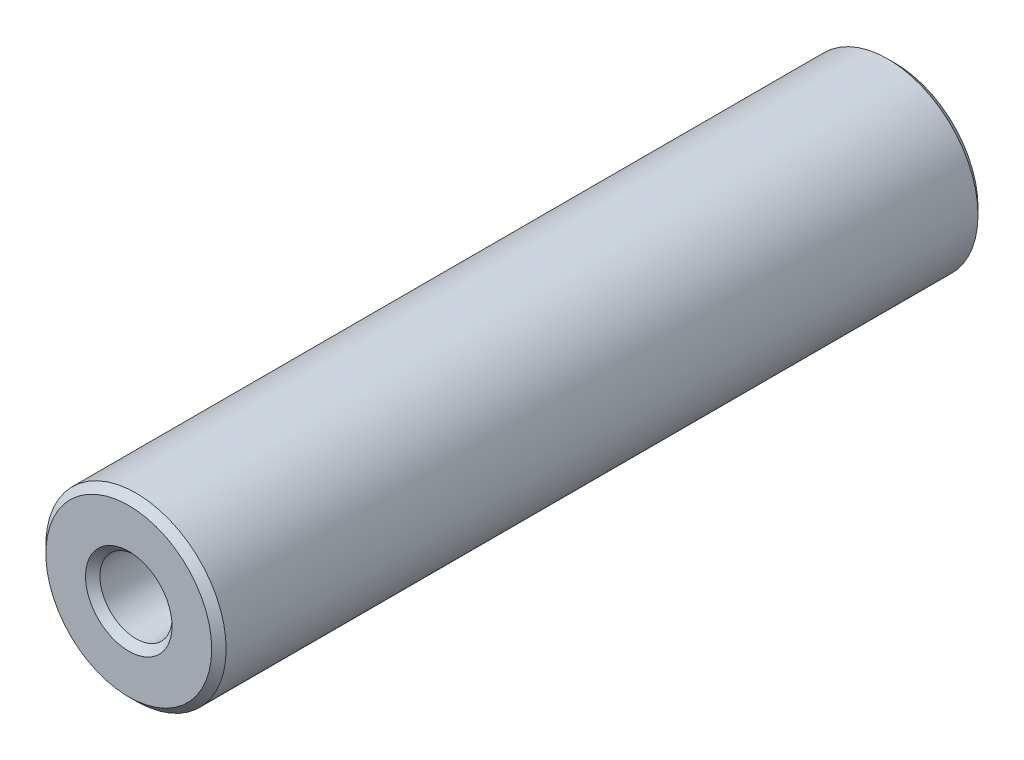
SolidWorks part; units mm, degrees
ref_plane "Front Plane" through (0, 0, 0) normal (0, 0, 1) x (1, 0, 0)
ref_plane "Top Plane" through (0, 0, 0) normal (0, 1, 0) x (1, 0, 0)
ref_plane "Right Plane" through (0, 0, 0) normal (1, 0, 0) x (0, 0, -1)
sketch "Sketch1" plane through (0, 0, 0) normal (0, 0, 1) x (1, 0, 0)
  circle A0 centre (0, 0) radius 6.35
  circle A1 centre (0, 0) radius 2.54
  dimension "D1" = 12.7
  dimension "D2" = 5.08
extrude "Boss-Extrude1" add sketch "Sketch1" along normal blind 53.975
chamfer "Chamfer1" distance 0.508 angle 45 4 edges at (2.54, 0, 0) (6.35, 0, 0) (2.54, 0, 53.975) (6.35, 0, 53.975)
